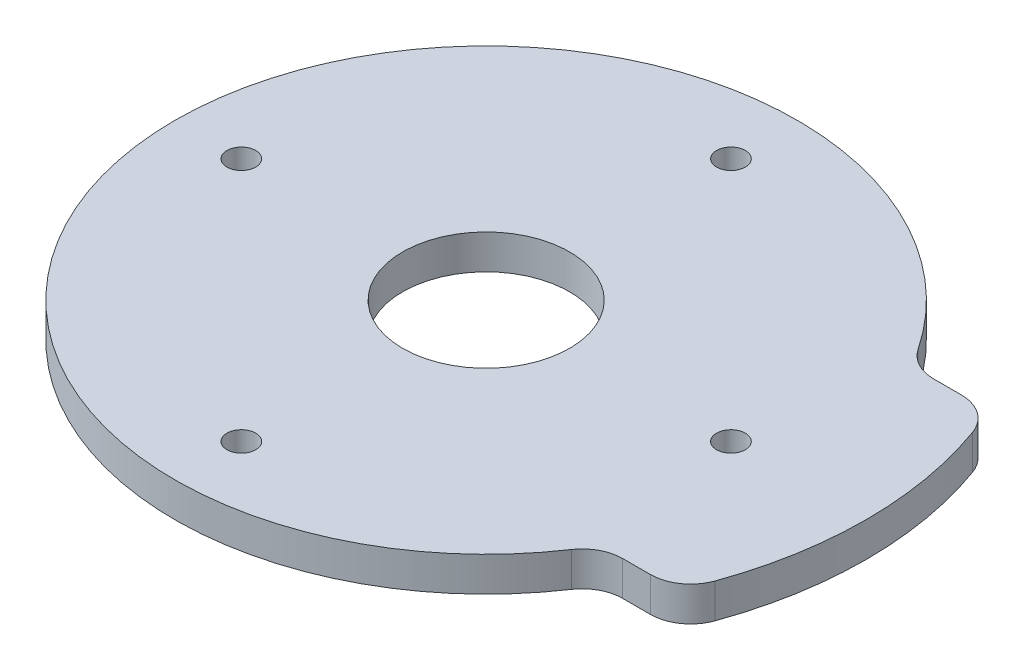
SolidWorks part; units mm, degrees
ref_plane "Спереди" through (0, 0, 0) normal (0, 0, 1) x (1, 0, 0)
ref_plane "Сверху" through (0, 0, 0) normal (0, 1, 0) x (1, 0, 0)
ref_plane "Справа" through (0, 0, 0) normal (1, 0, 0) x (0, 0, -1)
sketch "Эскиз1" plane through (0, 0, 0) normal (0, 1, 0) x (1, 0, 0)
  line L0 (0, 0) -> (66, 0) construction
  line L1 (60.2246, -27) -> (46.8231, -27)
  line L2 (60.2246, 27) -> (46.8231, 27)
  arc A0 (60.2246, -27) -> (60.2246, 27) centre (0, 0) ccw
  circle A1 centre (0, 0) radius 14.5
  arc A2 (46.8231, 27) -> (46.8231, -27) centre (0, 0) ccw
  dimension "D1" = 132
  dimension "D2" = 29
  dimension "D3" = 108.1
  dimension "D4" = 27
  dimension "D5" = 27
extrude "Бобышка-Вытянуть1" add sketch "Эскиз1" along normal blind 6
sketch "Эскиз2" plane through (0, 6, 0) normal (0, 1, 0) x (1, 0, 0)
  line L0 (0, 42.5) -> (0, -42.5) construction
  line L1 (0, -42.5) -> (42.5, 0) construction
  line L2 (42.5, 0) -> (-42.5, 0) construction
  circle A0 centre (0, 0) radius 42.5 construction
  circle A1 centre (0, 42.5) radius 2.5
  circle A2 centre (0, -42.5) radius 2.5
  circle A3 centre (-42.5, 0) radius 2.5
  circle A4 centre (42.5, 0) radius 2.5
  dimension "D1" = 85
  dimension "D2" = 5
  dimension "D3" = 5
  dimension "D4" = 5
  dimension "D5" = 5
extrude "Вырез-Вытянуть1" cut sketch "Эскиз2" against normal blind 10
fillet "Скругление1" radius 7 2 edges at (60.2246, 3, -27) (60.2246, 3, 27)
fillet "Скругление2" radius 7 2 edges at (46.8231, 3, -27) (46.8231, 3, 27)
